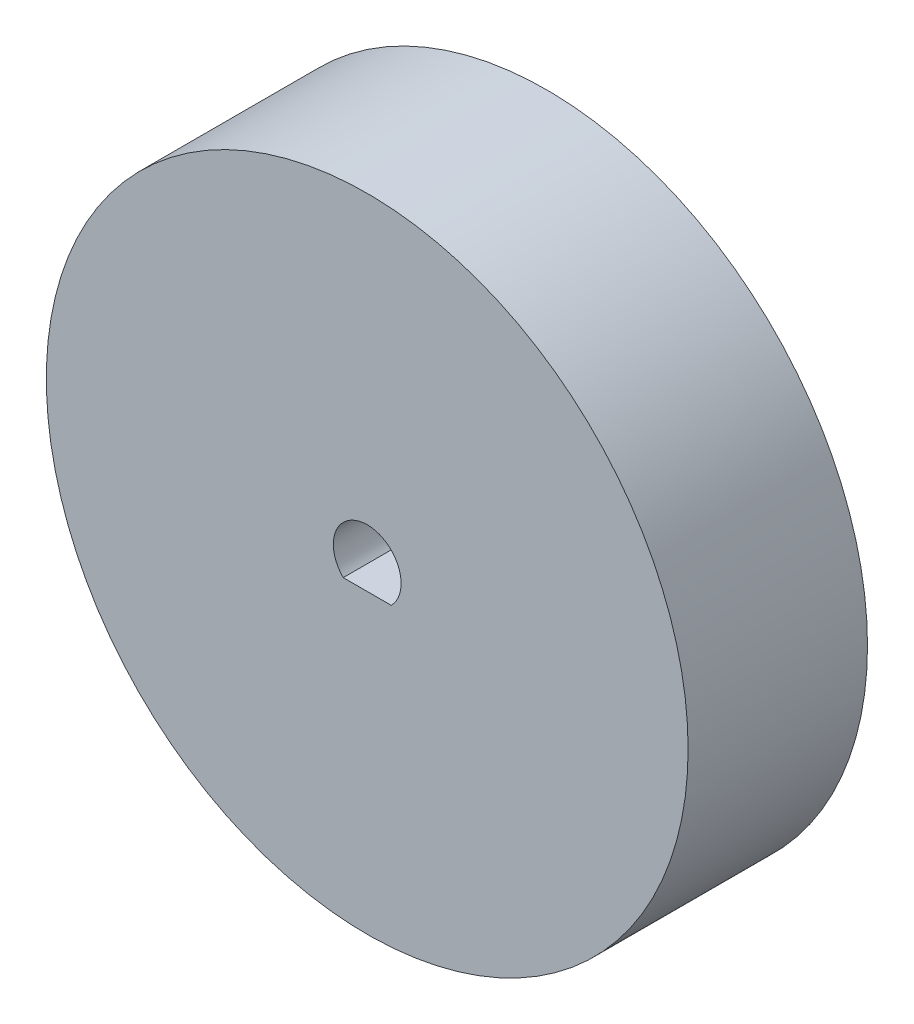
SolidWorks part; units mm, degrees
ref_plane "Front Plane" through (0, 0, 0) normal (0, 0, 1) x (1, 0, 0)
ref_plane "Top Plane" through (0, 0, 0) normal (0, 1, 0) x (1, 0, 0)
ref_plane "Right Plane" through (0, 0, 0) normal (1, 0, 0) x (0, 0, -1)
sketch "Sketch1" plane through (0, 0, 0) normal (0, 0, 1) x (1, 0, 0)
  line L0 (-1.2042, -1.2) -> (1.2042, -1.2)
  line L1 (-1.118, -1) -> (1.118, -1) construction
  line L2 (34.8491, -64.3018) -> (-16.1326, -6.01) construction
  circle A0 centre (0, 0) radius 16.1
  arc A1 (1.2042, -1.2) -> (-1.2042, -1.2) centre (0, 0) ccw
  arc A2 (1.118, -1) -> (-1.118, -1) centre (0, 0) ccw construction
  point P4 (-1.2042, -1.2)
  point P5 (1.2042, -1.2)
  point P10 (0, 1.5)
  dimension "D1" = 0.2
  dimension "D3" = 1.5
  dimension "D2" = 2.5
extrude "Boss-Extrude1" add sketch "Sketch1" along normal blind 9
